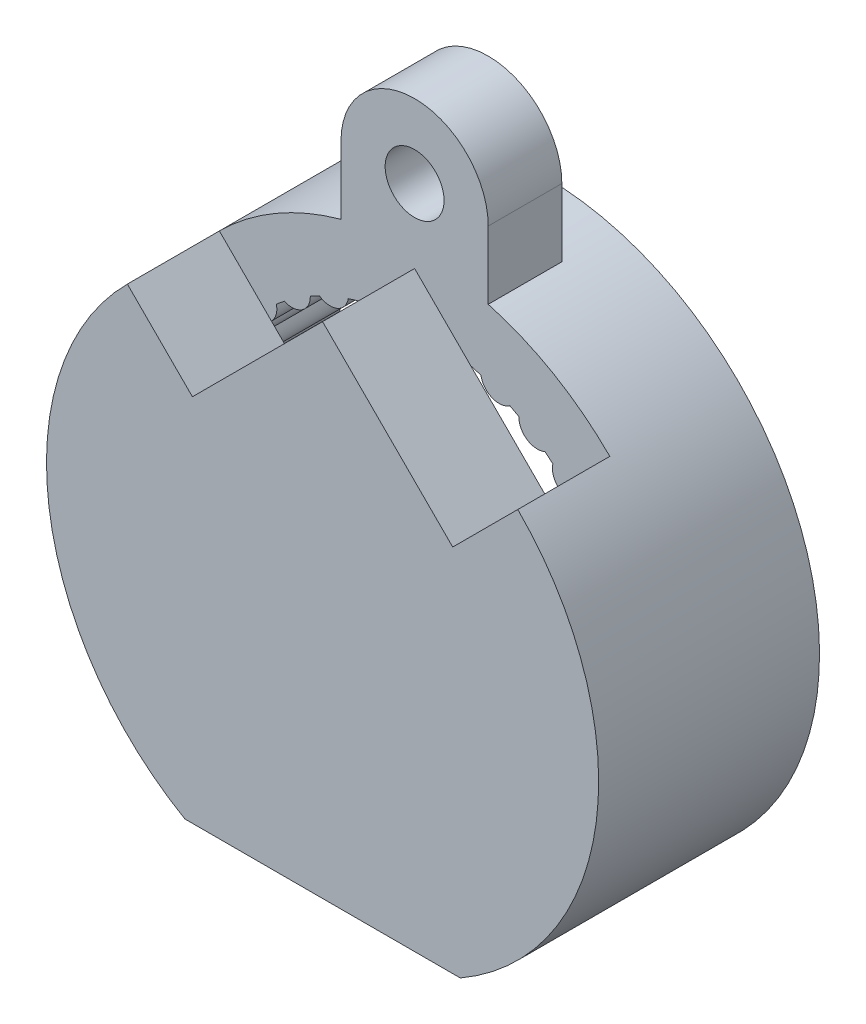
SolidWorks part; units mm, degrees
ref_plane "Front Plane" through (0, 0, 0) normal (0, 0, 1) x (1, 0, 0)
ref_plane "Top Plane" through (0, 0, 0) normal (0, 1, 0) x (1, 0, 0)
ref_plane "Right Plane" through (0, 0, 0) normal (1, 0, 0) x (0, 0, -1)
sketch "Sketch1" plane through (0, 0, 0) normal (0, 0, 1) x (1, 0, 0)
  circle A0 centre (0, 0) radius 11 construction
  circle A1 centre (0, 0) radius 12 construction
  circle A2 centre (12, 0) radius 1
  circle A3 centre (0, 0) radius 11 construction
  circle A4 centre (11.7694, -2.3411) radius 1
  circle A5 centre (11.0866, -4.5922) radius 1
  circle A6 centre (9.9776, -6.6668) radius 1
  circle A7 centre (8.4853, -8.4853) radius 1
  circle A8 centre (6.6668, -9.9776) radius 1
  circle A9 centre (4.5922, -11.0866) radius 1
  circle A10 centre (2.3411, -11.7694) radius 1
  circle A11 centre (0, -12) radius 1
  circle A12 centre (-2.3411, -11.7694) radius 1
  circle A13 centre (-4.5922, -11.0866) radius 1
  circle A14 centre (-6.6668, -9.9776) radius 1
  circle A15 centre (-8.4853, -8.4853) radius 1
  circle A16 centre (-9.9776, -6.6668) radius 1
  circle A17 centre (-11.0866, -4.5922) radius 1
  circle A18 centre (-11.7694, -2.3411) radius 1
  circle A19 centre (-12, 0) radius 1
  circle A20 centre (-11.7694, 2.3411) radius 1
  circle A21 centre (-11.0866, 4.5922) radius 1
  circle A22 centre (-9.9776, 6.6668) radius 1
  circle A23 centre (-8.4853, 8.4853) radius 1
  circle A24 centre (-6.6668, 9.9776) radius 1
  circle A25 centre (-4.5922, 11.0866) radius 1
  circle A26 centre (-2.3411, 11.7694) radius 1
  circle A27 centre (0, 12) radius 1
  circle A28 centre (2.3411, 11.7694) radius 1
  circle A29 centre (4.5922, 11.0866) radius 1
  circle A30 centre (6.6668, 9.9776) radius 1
  circle A31 centre (8.4853, 8.4853) radius 1
  circle A32 centre (9.9776, 6.6668) radius 1
  circle A33 centre (11.0866, 4.5922) radius 1
  circle A34 centre (11.7694, 2.3411) radius 1
  point P71 (0, 0)
  dimension "D1" = 22
  dimension "D2" = 2
  dimension "D3" = 22
  dimension "D4" = 32
extrude "Boss-Extrude1" add sketch "Sketch1" along normal mid plane 7
sketch "Sketch2" plane through (0, 0, 0) normal (0, 0, 1) x (1, 0, 0)
  circle A0 centre (0, 0) radius 11.5
  circle A1 centre (0, 0) radius 15
  dimension "D1" = 23
  dimension "D3" = 30
extrude "Boss-Extrude2" add sketch "Sketch2" against normal mid plane 7
sketch "Sketch3" plane through (0, 0, -3.5) normal (0, 0, -1) x (-1, 0, 0)
  line L0 (0, 18.14) -> (0, 0) construction
  line L1 (4, 18.14) -> (4, 14.4568)
  line L5 (-4, 14.4568) -> (-4, 18.14)
  arc A0 (-4, 18.14) -> (4, 18.14) centre (0, 18.14) ccw construction
  arc A1 (4, 18.14) -> (-4, 18.14) centre (0, 18.14) ccw
  circle A2 centre (0, 18.14) radius 1.6
  circle A3 centre (0, 0) radius 15 construction
  arc A4 (-4, 14.4568) -> (4, 14.4568) centre (0, 0) cw
  dimension "D2" = 3.2
  dimension "D3" = 8
  dimension "D1" = 18.14
extrude "Boss-Extrude5" add sketch "Sketch3" along normal blind 4 from surface at -7 contours L5 A4 L1 A1 A2 starting at face at (0, 0, 3.5)
sketch "Sketch4" plane through (0, 0, 3.5) normal (0, 0, 1) x (1, 0, 0)
  line L0 (-7.7782, 6.364) -> (0, 14.1421)
  line L1 (0, 14.1421) -> (7.7782, 6.364)
  line L2 (-7.7782, 6.364) -> (0, -1.4142) construction
  line L3 (0, -1.4142) -> (7.7782, 6.364) construction
  line L5 (-7.0711, 7.0711) -> (0, 0) construction
  line L6 (0, 0) -> (7.0711, 7.0711) construction
  arc A1 (7.7782, 6.364) -> (-7.7782, 6.364) centre (0, -2.9021) ccw construction
  circle A2 centre (0, 0) radius 15 construction
  arc A3 (-7.7782, 6.364) -> (7.7782, 6.364) centre (0, -2.9021) ccw
  dimension "D1" = 1
  dimension "D2" = 10
extrude "Boss-Extrude4" add sketch "Sketch4" along normal blind 5
sketch "Sketch5" plane through (0, 0, 8.5) normal (0, 0, 1) x (1, 0, 0)
  line L0 (-7.4833, -13) -> (7.4833, -13)
  arc A0 (-4, 14.4568) -> (0, -15) centre (0, 0) ccw construction
  arc A1 (0, -15) -> (4, 14.4568) centre (0, 0) ccw construction
  arc A41 (-7.4833, -13) -> (0, -15) centre (0, 0) ccw
  arc A42 (0, -15) -> (7.4833, -13) centre (0, 0) ccw
  dimension "D1" = 2
extrude "Cut-Extrude1" cut sketch "Sketch5" against normal through all both and the other way through all
sketch "Sketch6" plane through (0, 0, 3.5) normal (0, 0, 1) x (1, 0, 0)
  line L0 (7.0711, 7.0711) -> (10.6066, 10.6066)
  line L2 (-10.6066, 10.6066) -> (-7.0711, 7.0711)
  line L3 (-10.6066, 10.6066) -> (10.6066, 10.6066) construction
  line L4 (-7.0711, 7.0711) -> (-7.7782, 6.364)
  line L5 (0, 14.1421) -> (-7.7782, 6.364) construction
  line L6 (-6.6627, -13) -> (6.6627, -13)
  line L7 (7.7782, 6.364) -> (0, 14.1421)
  line L8 (6.6627, -13) -> (7.4833, -13)
  line L9 (4, 14.4568) -> (4, 18.14)
  line L10 (-4, 18.14) -> (-4, 14.4568)
  line L11 (-7.4833, -13) -> (-6.6627, -13)
  line L12 (-3.0638, 11.0783) -> (0, 14.1421)
  line L14 (0, 14.1421) -> (3.0638, 11.0783)
  line L16 (6.6627, -13) -> (7.4833, -13)
  line L19 (-7.4833, -13) -> (-6.6627, -13)
  line L24 (0, 14.1421) -> (-7.7782, 6.364)
  line L26 (7.7782, 6.364) -> (7.0711, 7.0711)
  line L27 (-7.0711, 7.0711) -> (0, 0) construction
  line L28 (0, 0) -> (7.0711, 7.0711) construction
  line L37 (-3.0684, 11.0831) -> (-3.0638, 11.0783)
  line L38 (3.0638, 11.0783) -> (3.0684, 11.0831)
  arc A2 (6.6627, -13) -> (7.7782, 6.364) centre (0, -2.9021) ccw
  arc A3 (-7.7782, 6.364) -> (-6.6627, -13) centre (0, -2.9021) ccw
  arc A4 (6.6627, -13) -> (7.7782, 6.364) centre (0, -2.9021) ccw
  arc A5 (-7.7782, 6.364) -> (-6.6627, -13) centre (0, -2.9021) ccw
  arc A39 (7.4833, -13) -> (4, 14.4568) centre (0, 0) ccw
  arc A40 (4, 18.14) -> (-4, 18.14) centre (0, 18.14) ccw
  arc A41 (-4, 14.4568) -> (-7.4833, -13) centre (0, 0) ccw
  arc A42 (-11.4582, 0.9799) -> (-6.6627, -13) centre (0, -2.9021) ccw
  arc A43 (-11.4137, 1.4065) -> (-11.4582, 0.9799) centre (0, 0) ccw
  arc A44 (-11.4137, 1.4065) -> (-11.2808, 1.4686) centre (-11.7694, 2.3411) ccw
  arc A45 (-10.794, 2.5614) -> (-11.2808, 1.4686) centre (0, -2.9021) ccw
  arc A46 (-10.794, 2.5614) -> (-11.0831, 3.0684) centre (-11.7694, 2.3411) ccw
  arc A47 (-10.92, 3.6062) -> (-11.0831, 3.0684) centre (0, 0) ccw
  arc A48 (-10.92, 3.6062) -> (-10.2715, 5.1716) centre (-11.0866, 4.5922) ccw
  arc A49 (-10.0066, 5.6673) -> (-10.2715, 5.1716) centre (0, 0) ccw
  arc A50 (-10.0066, 5.6673) -> (-9.0652, 7.0761) centre (-9.9776, 6.6668) ccw
  arc A51 (-8.7087, 7.5106) -> (-9.0652, 7.0761) centre (0, 0) ccw
  arc A52 (-8.7087, 7.5106) -> (-7.5106, 8.7087) centre (-8.4853, 8.4853) ccw
  arc A53 (-7.0761, 9.0652) -> (-7.5106, 8.7087) centre (0, 0) ccw
  arc A54 (-7.0761, 9.0652) -> (-5.6673, 10.0066) centre (-6.6668, 9.9776) ccw
  arc A55 (-5.1716, 10.2715) -> (-5.6673, 10.0066) centre (0, 0) ccw
  arc A56 (-5.1716, 10.2715) -> (-3.6062, 10.92) centre (-4.5922, 11.0866) ccw
  arc A58 (-3.0684, 11.0831) -> (-3.6062, 10.92) centre (0, 0) ccw
  arc A61 (3.6062, 10.92) -> (3.0684, 11.0831) centre (0, 0) ccw
  arc A62 (3.6062, 10.92) -> (5.1716, 10.2715) centre (4.5922, 11.0866) ccw
  arc A64 (5.6673, 10.0066) -> (5.1716, 10.2715) centre (0, 0) ccw
  arc A65 (5.6673, 10.0066) -> (7.0761, 9.0652) centre (6.6668, 9.9776) ccw
  arc A66 (7.5106, 8.7087) -> (7.0761, 9.0652) centre (0, 0) ccw
  arc A67 (7.5106, 8.7087) -> (8.7087, 7.5106) centre (8.4853, 8.4853) ccw
  arc A68 (9.0652, 7.0761) -> (8.7087, 7.5106) centre (0, 0) ccw
  arc A69 (9.0652, 7.0761) -> (10.0066, 5.6673) centre (9.9776, 6.6668) ccw
  arc A70 (10.2715, 5.1716) -> (10.0066, 5.6673) centre (0, 0) ccw
  arc A71 (10.2715, 5.1716) -> (10.92, 3.6062) centre (11.0866, 4.5922) ccw
  arc A72 (11.0831, 3.0684) -> (10.92, 3.6062) centre (0, 0) ccw
  arc A73 (11.0831, 3.0684) -> (10.794, 2.5614) centre (11.7694, 2.3411) ccw
  arc A74 (11.2808, 1.4686) -> (10.794, 2.5614) centre (0, -2.9021) ccw
  arc A75 (11.2808, 1.4686) -> (11.4137, 1.4065) centre (11.7694, 2.3411) ccw
  arc A76 (11.4582, 0.9799) -> (11.4137, 1.4065) centre (0, 0) ccw
  arc A77 (6.6627, -13) -> (11.4582, 0.9799) centre (0, -2.9021) ccw
  arc A78 (7.4833, -13) -> (10.6066, 10.6066) centre (0, 0) ccw
  arc A80 (-10.6066, 10.6066) -> (-7.4833, -13) centre (0, 0) ccw
  point P20 (0, 10.6066)
  dimension "D1" = 0
  dimension "D2" = 0
extrude "Boss-Extrude6" add sketch "Sketch6" along normal up to surface (5 mm away) up to face at (0, 0.0621, 8.5)
